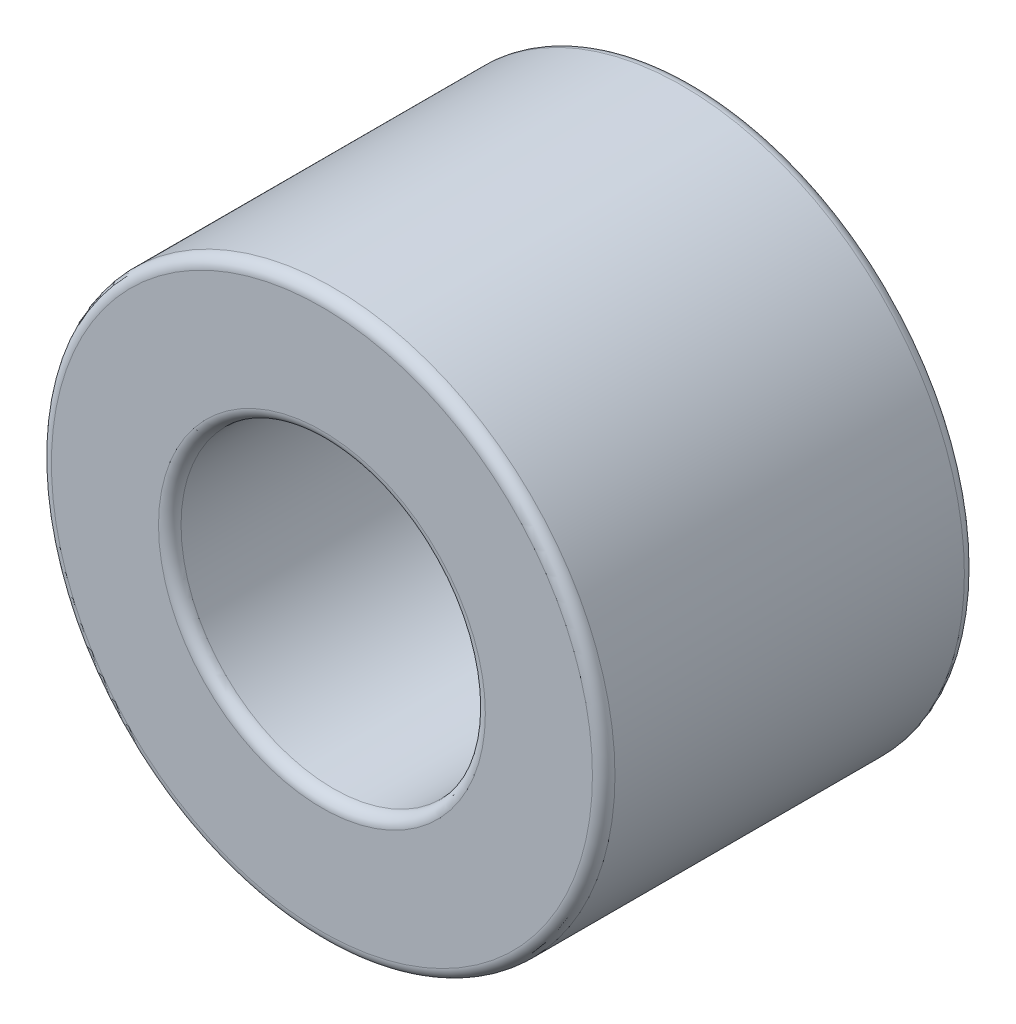
SolidWorks part; units mm, degrees
ref_plane "Front Plane" through (0, 0, 0) normal (0, 0, 1) x (1, 0, 0)
ref_plane "Top Plane" through (0, 0, 0) normal (0, 1, 0) x (1, 0, 0)
ref_plane "Right Plane" through (0, 0, 0) normal (1, 0, 0) x (0, 0, -1)
sketch "Sketch1" plane through (0, 0, 0) normal (0, 0, 1) x (1, 0, 0)
  circle A0 centre (0, 0) radius 1.7145
  circle A1 centre (0, 0) radius 3.175
  dimension "D1" = 6.35
  dimension "D2" = 3.429
extrude "Boss-Extrude1" add sketch "Sketch1" along normal blind 4.191
fillet "Fillet1" radius 0.127 4 edges at (1.7145, 0, 0) (3.175, 0, 0) (3.175, 0, 4.191) (1.7145, 0, 4.191)
